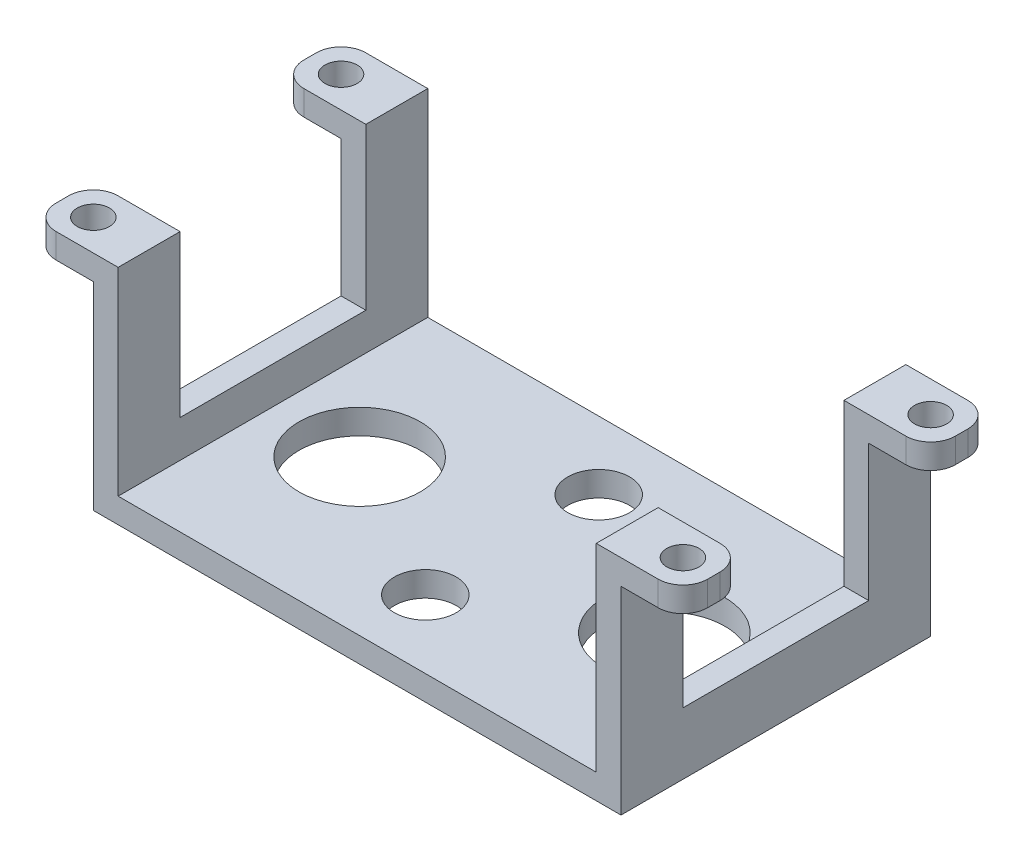
SolidWorks part; units mm, degrees
ref_plane "Płaszczyzna przednia" through (0, 0, 0) normal (0, 0, 1) x (1, 0, 0)
ref_plane "Płaszczyzna górna" through (0, 0, 0) normal (0, 1, 0) x (1, 0, 0)
ref_plane "Płaszczyzna prawa" through (0, 0, 0) normal (1, 0, 0) x (0, 0, -1)
sketch "Szkic1" plane through (0, 0, 0) normal (0, 1, 0) x (1, 0, 0)
  line L1 (21.3, -12.5) -> (-21.3, -12.5)
  line L2 (21.3, -12.5) -> (21.3, 12.5)
  line L3 (21.3, 12.5) -> (-21.3, 12.5)
  line L4 (-21.3, -12.5) -> (-21.3, 12.5)
  line L5 (21.3, -12.5) -> (-21.3, 12.5) construction
  line L6 (21.3, 12.5) -> (-21.3, -12.5) construction
  point P0 (0, 0)
  dimension "D1" = 25
  dimension "D2" = 42.6
extrude "Dodanie-wyciągnięcie2" add sketch "Szkic1" along normal blind 18
shell "Skorupa5" thickness 2
sketch "Szkic2" plane through (0, 18, 0) normal (0, 1, 0) x (1, 0, 0)
  line L0 (-21.3, 12.5) -> (-21.3, -12.5) construction
  line L1 (-21.3, 12.5) -> (-24.3, 12.5)
  line L2 (-21.3, 12.5) -> (-21.3, 7.5)
  line L3 (-21.3, 7.5) -> (-24.3, 7.5)
  line L4 (-26.3, 10.5) -> (-26.3, 9.5)
  line L5 (-26.3, 12.5) -> (-21.3, 7.5) construction
  line L6 (-26.3, 7.5) -> (-21.3, 12.5) construction
  line L7 (0, 12.5) -> (0, -12.5) construction
  line L8 (19.3, 12.5) -> (-19.3, 12.5) construction
  line L9 (-19.3, -12.5) -> (19.3, -12.5) construction
  line L10 (-19.3, 0) -> (19.3, 0) construction
  line L11 (-19.3, 12.5) -> (-19.3, -12.5) construction
  line L12 (19.3, -12.5) -> (19.3, 12.5) construction
  line L13 (-21.3, -7.5) -> (-24.3, -7.5)
  line L14 (-26.3, -10.5) -> (-26.3, -9.5)
  line L15 (-21.3, -12.5) -> (-24.3, -12.5)
  line L16 (-21.3, -12.5) -> (-21.3, -7.5)
  line L17 (21.3, -12.5) -> (21.3, -7.5)
  line L18 (21.3, -12.5) -> (24.3, -12.5)
  line L19 (26.3, -10.5) -> (26.3, -9.5)
  line L20 (21.3, -7.5) -> (24.3, -7.5)
  line L21 (21.3, 7.5) -> (24.3, 7.5)
  line L22 (26.3, 10.5) -> (26.3, 9.5)
  line L23 (21.3, 12.5) -> (24.3, 12.5)
  line L24 (21.3, 12.5) -> (21.3, 7.5)
  circle A0 centre (-23.8, 10) radius 1.3
  arc A1 (-24.3, 7.5) -> (-26.3, 9.5) centre (-24.3, 9.5) cw
  arc A2 (-24.3, 12.5) -> (-26.3, 10.5) centre (-24.3, 10.5) ccw
  arc A3 (-24.3, -7.5) -> (-26.3, -9.5) centre (-24.3, -9.5) ccw
  arc A4 (-24.3, -12.5) -> (-26.3, -10.5) centre (-24.3, -10.5) cw
  circle A5 centre (-23.8, -10) radius 1.3
  circle A6 centre (23.8, -10) radius 1.3
  arc A7 (24.3, -12.5) -> (26.3, -10.5) centre (24.3, -10.5) ccw
  arc A8 (24.3, -7.5) -> (26.3, -9.5) centre (24.3, -9.5) cw
  arc A9 (24.3, 7.5) -> (26.3, 9.5) centre (24.3, 9.5) ccw
  arc A10 (24.3, 12.5) -> (26.3, 10.5) centre (24.3, 10.5) cw
  circle A11 centre (23.8, 10) radius 1.3
  dimension "D3" = 2
  dimension "D1" = 5
  dimension "D2" = 5
  dimension "D4" = 7.5
extrude "Dodanie-wyciągnięcie3" add sketch "Szkic2" against normal blind 2
sketch "Szkic3" plane through (0, 2, 0) normal (0, 1, 0) x (1, 0, 0)
  line L0 (-19.3, 12.5) -> (-19.3, -12.5) construction
  circle A0 centre (-12.3, 0) radius 4.9
  circle A1 centre (12.3, 0) radius 4.9
  circle A2 centre (0, 7) radius 2.5
  circle A3 centre (0, -7) radius 2.5
  point P9 (0, 0)
  point P14 (0, 0)
  dimension "D1" = 7
  dimension "D3" = 9.8
  dimension "D4" = 5
  dimension "D5" = 7
  dimension "D2" = 2
  dimension "D6" = 2
extrude "Wytnij-wyciągnięcie1" cut sketch "Szkic3" against normal blind 2
sketch "Szkic4" plane through (-21.3, 0, 0) normal (-1, 0, 0) x (0, 0, 1)
  line L0 (-7.5, 18) -> (7.5, 18) construction
  line L1 (7.5, 5) -> (-7.5, 5)
  line L2 (7.5, 5) -> (7.5, 18)
  line L3 (7.5, 18) -> (-7.5, 18)
  line L4 (-7.5, 5) -> (-7.5, 18)
  line L5 (7.5, 5) -> (-7.5, 18) construction
  line L6 (7.5, 18) -> (-7.5, 5) construction
  point P0 (0, 11.5)
  dimension "D1" = 15
  dimension "D2" = 13
extrude "Wytnij-wyciągnięcie2" cut sketch "Szkic4" against normal through all both and the other way through all
